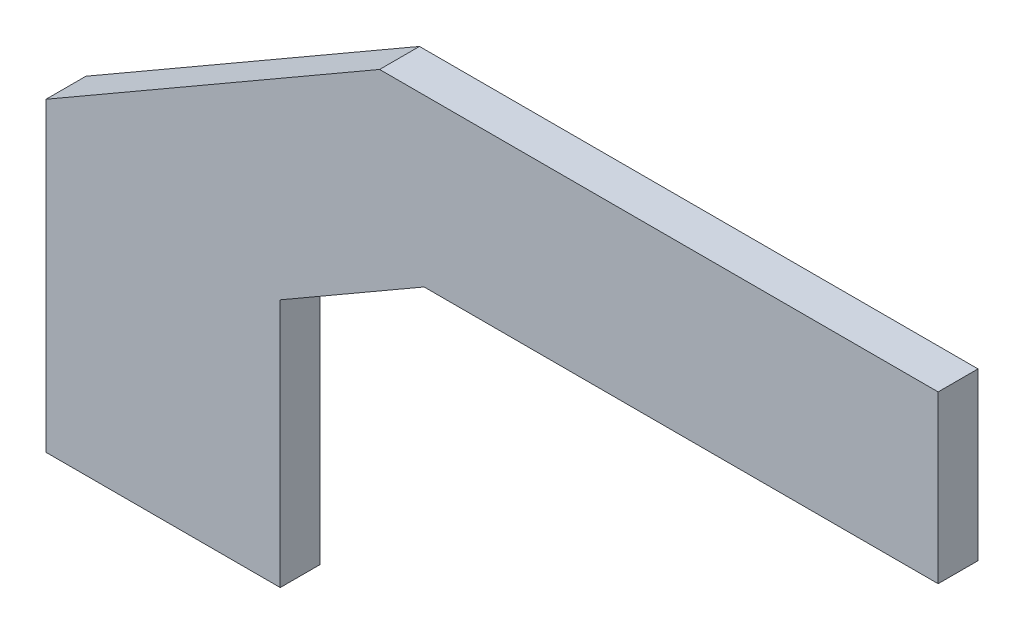
SolidWorks part; units mm, degrees
material "PBT General Purpose"
ref_plane "Front Plane" through (0, 0, 0) normal (0, 0, 1) x (1, 0, 0)
ref_plane "Top Plane" through (0, 0, 0) normal (0, 1, 0) x (1, 0, 0)
ref_plane "Right Plane" through (0, 0, 0) normal (1, 0, 0) x (0, 0, -1)
sketch "Sketch1" plane through (0, 0, 0) normal (0, 0, 1) x (1, 0, 0)
  line L7 (0, 0) -> (1.41, 0)
  line L8 (1.41, 0) -> (1.41, 1.5)
  line L9 (1.41, 1.5) -> (2.276, 2)
  line L10 (2.276, 2) -> (5.37, 2)
  line L11 (5.37, 2) -> (5.37, 3)
  line L12 (5.37, 3) -> (2.0081, 3)
  line L13 (2.0081, 3) -> (0, 1.8406)
  line L14 (0, 1.8406) -> (0, 0)
  point P2 (4.2004, 3.5761)
  point P8 (3.0907, 3.7779)
  point P11 (3.6581, 2.7943)
  point P12 (0, 1.7855)
  dimension "D1" = 1.41
  dimension "D2" = 1
  dimension "D3" = 1.5
  dimension "D4" = 3.96
  dimension "D5" = 1
  dimension "D6" = 3
  dimension "D7" = 1
extrude "Boss-Extrude1" add sketch "Sketch1" along normal mid plane 0.24 contours L10 L11 L12 L13 L14 L7 L8 L9
